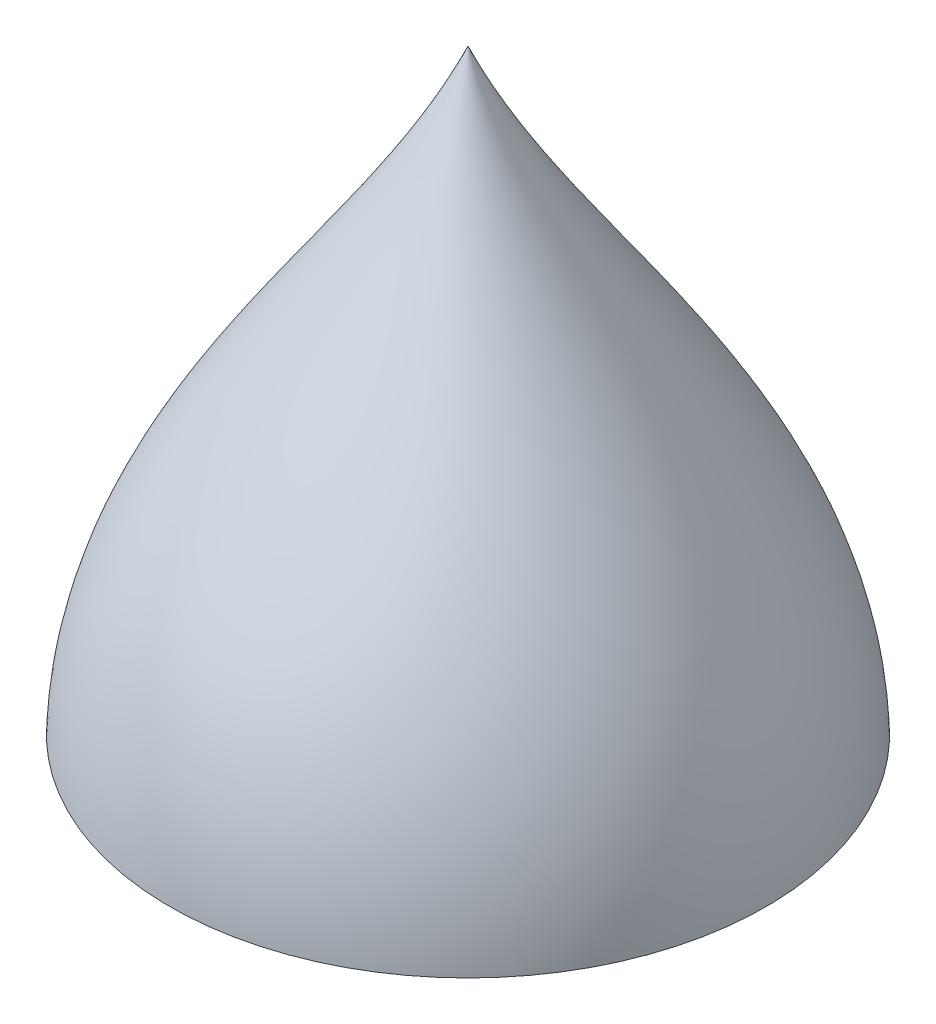
SolidWorks part; units mm, degrees
ref_plane "Front Plane" through (0, 0, 0) normal (0, 0, 1) x (1, 0, 0)
ref_plane "Top Plane" through (0, 0, 0) normal (0, 1, 0) x (1, 0, 0)
ref_plane "Right Plane" through (0, 0, 0) normal (1, 0, 0) x (0, 0, -1)
sketch "Sketch1" plane through (0, 0, 0) normal (0, 0, 1) x (1, 0, 0)
  line L0 (0, 0) -> (0, 8) construction
  line L1 (0, 8) -> (-4, 0) construction
  line L2 (-4, 0) -> (-3.1, 0)
  line L3 (-2, 1) -> (-2, 0)
  line L4 (-2, 0) -> (0, 0)
  line L5 (0, 0) -> (0, 8)
  line L6 (-3.1, 0) -> (-3.1, 1)
  line L7 (-3.1, 1) -> (-2, 1)
  spline S0 degree 3 poles (-4, 0) (-3.8867, 3.1201) (-1.1769, 5.3229) (0, 8) knots 0 0 0 0 1 1 1 1
  dimension "D1" = 8
  dimension "D2" = 4
  dimension "D3" = 3.1
  dimension "D4" = 2
  dimension "D5" = 1
revolve "Revolve1" add sketch "Sketch1" angle 360 about L5
